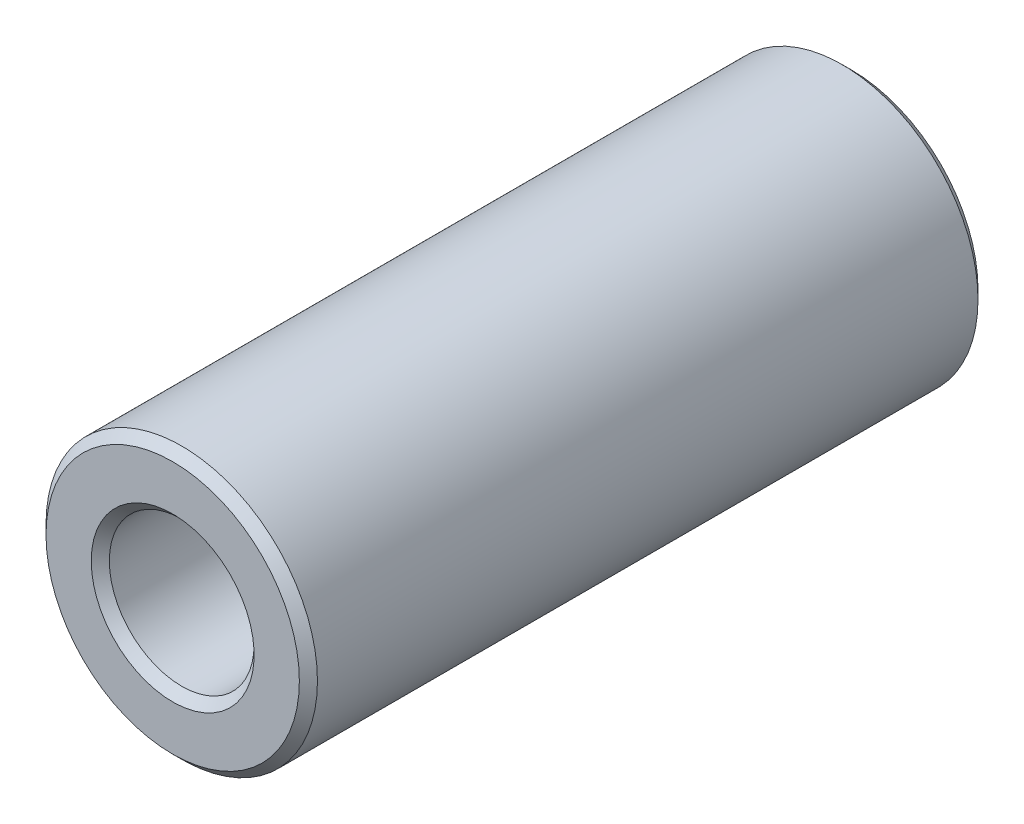
SolidWorks part; units mm, degrees
material "KS26"
ref_plane "正面" through (0, 0, 0) normal (0, 0, 1) x (1, 0, 0)
ref_plane "平面" through (0, 0, 0) normal (0, 1, 0) x (1, 0, 0)
ref_plane "右側面" through (0, 0, 0) normal (1, 0, 0) x (0, 0, -1)
sketch "ｽｹｯﾁ1" plane through (0, 0, 0) normal (1, 0, 0) x (0, 0, -1)
  line L0 (-7.1281, 0) -> (7.8719, 0) construction
  line L1 (0, 1.6) -> (0, 0) construction
  line L2 (-7.5, 3) -> (7.5, 3)
  line L3 (-7.5, 3) -> (-7.5, 1.6)
  line L4 (-7.5, 1.6) -> (7.5, 1.6)
  line L5 (7.5, 3) -> (7.5, 1.6)
  dimension "D1" = 15
  dimension "D2" = 6
  dimension "D3" = 3.2
revolve "回転1" add sketch "ｽｹｯﾁ1" angle 360 about L0
chamfer "面取り1" distance 0.2 angle 45 4 edges at (1.6, 0, 7.5) (1.6, 0, -7.5) (3, 0, -7.5) (3, 0, 7.5)
